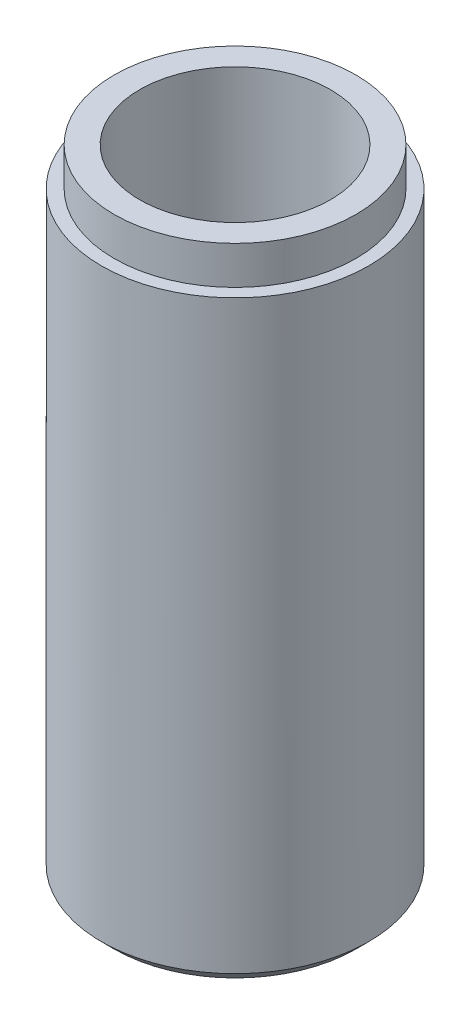
SolidWorks part; units mm, degrees
ref_plane "Плоскость1" through (0, 0, 0) normal (0, 0, 1) x (1, 0, 0)
ref_plane "Плоскость2" through (0, 0, 0) normal (0, 1, 0) x (1, 0, 0)
ref_plane "Плоскость3" through (0, 0, 0) normal (1, 0, 0) x (0, 0, -1)
sketch "Эскиз1" plane through (0, 0, 0) normal (0, 0, 1) x (1, 0, 0)
  line L0 (0, 0) -> (0, 98.5138) construction
  line L1 (7.5, 0) -> (7.5, 50)
  line L2 (7.5, 50) -> (10.5, 50)
  line L5 (10.5, 50) -> (10.5, 0)
  line L6 (10.5, 0) -> (7.5, 0)
  dimension "D1" = 15
  dimension "D2" = 50
  dimension "D4" = 21
revolve "Повернуть1" add sketch "Эскиз1" angle 360 about L0
cosmetic thread "Условное изображение резьбы2" parameters "D1"=35, "D2"=19
chamfer "Фаска1" distance 1 angle 45 1 edges at (0, 0, -10.5)
sketch "Эскиз2" plane through (0, 50, 0) normal (0, 1, 0) x (1, 0, 0)
  circle A0 centre (0, 0) radius 9.5
  dimension "D1" = 19
extrude "Вытянуть1" cut sketch "Эскиз2" against normal blind 3 flip side to cut
